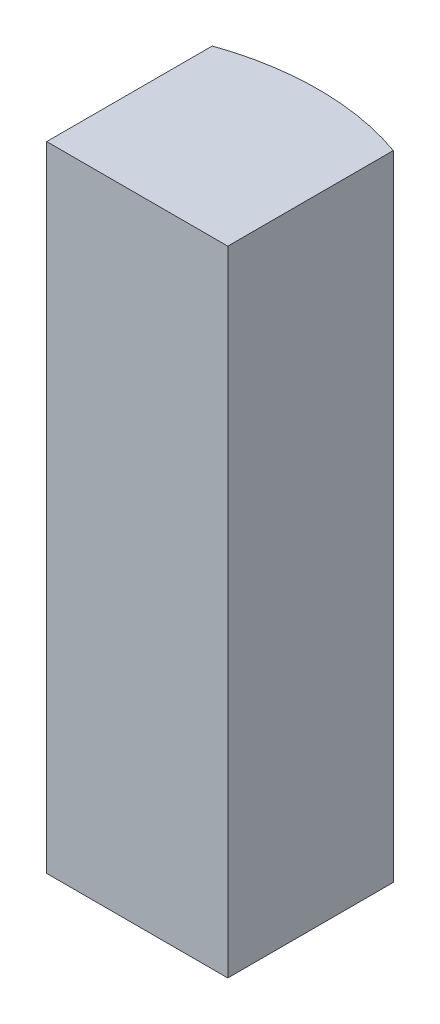
SolidWorks part; units mm, degrees
ref_plane "前视基准面" through (0, 0, 0) normal (0, 0, 1) x (1, 0, 0)
ref_plane "上视基准面" through (0, 0, 0) normal (0, 1, 0) x (1, 0, 0)
ref_plane "右视基准面" through (0, 0, 0) normal (1, 0, 0) x (0, 0, -1)
sketch "草图1" plane through (0, 0, 0) normal (0, 1, 0) x (1, 0, 0)
  line L0 (-56.5685, -20) -> (56.5685, -20)
  line L1 (-56.5685, 20) -> (56.5685, 20)
  line L2 (-20, 56.5685) -> (-20, -56.5685)
  line L3 (20, 56.5685) -> (20, -56.5685)
  circle A0 centre (0, 0) radius 60
  dimension "D1" = 120
  dimension "D2" = 20
  dimension "D3" = 20
  dimension "D4" = 20
  dimension "D5" = 20
extrude "凸台-拉伸1" add sketch "草图1" along normal blind 140 contours L3 A0 L2 L1
